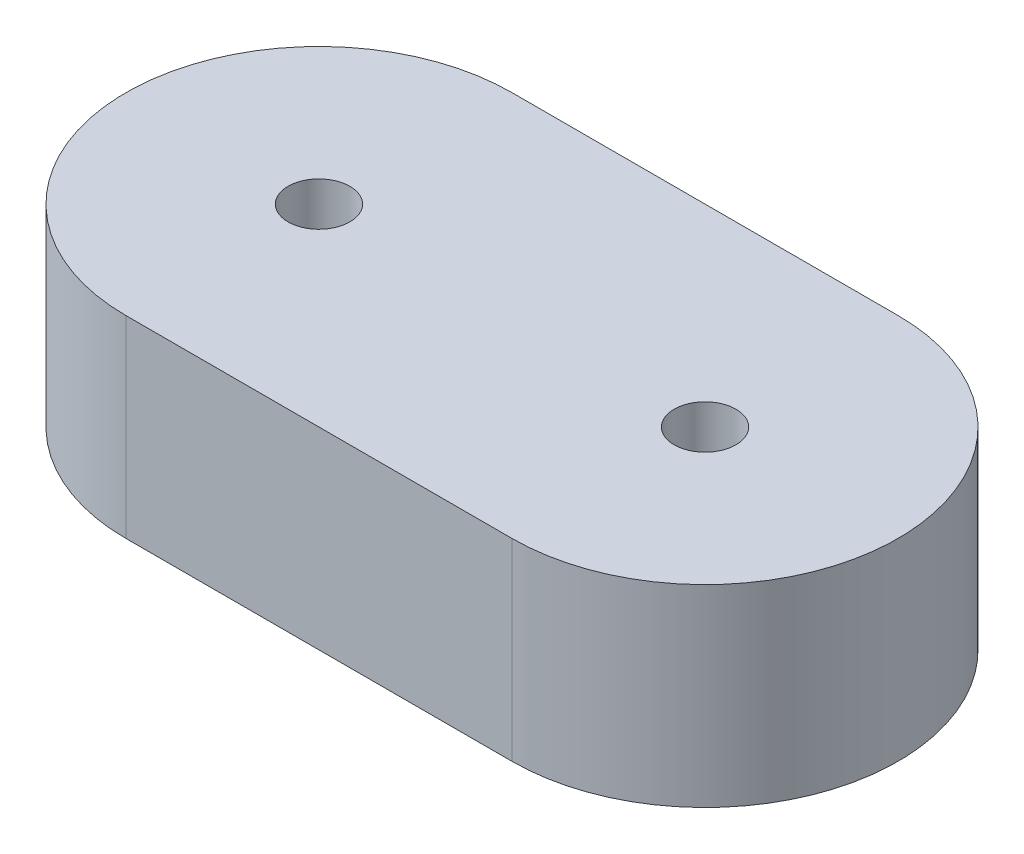
SolidWorks part; units mm, degrees
material "Acrylic (Medium-high impact)"
ref_plane "Front Plane" through (0, 0, 0) normal (0, 0, 1) x (1, 0, 0)
ref_plane "Top Plane" through (0, 0, 0) normal (0, 1, 0) x (1, 0, 0)
ref_plane "Right Plane" through (0, 0, 0) normal (1, 0, 0) x (0, 0, -1)
sketch "Sketch1" plane through (0, 0, 0) normal (0, 1, 0) x (1, 0, 0)
  line L0 (-10, 0) -> (10, 0) construction
  line L1 (-10, 10) -> (10, 10)
  line L2 (-10, -10) -> (10, -10)
  arc A0 (-10, 10) -> (-10, -10) centre (-10, 0) ccw
  arc A1 (10, -10) -> (10, 10) centre (10, 0) ccw
  circle A2 centre (-10, 0) radius 1.6
  circle A3 centre (10, 0) radius 1.6
  point P2 (0, 0)
  dimension "D2" = 3.2
  dimension "D1" = 20
  dimension "D3" = 20
extrude "Boss-Extrude1" add sketch "Sketch1" along normal blind 10
